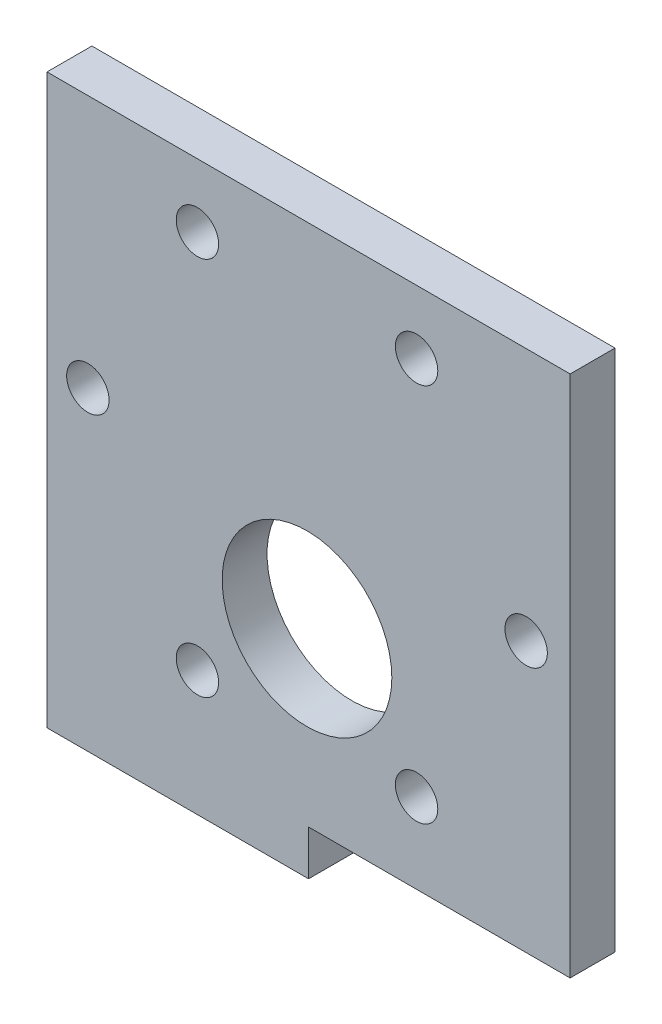
SolidWorks part; units mm, degrees
ref_plane "Front Plane" through (0, 0, 0) normal (0, 0, 1) x (1, 0, 0)
ref_plane "Top Plane" through (0, 0, 0) normal (0, 1, 0) x (1, 0, 0)
ref_plane "Right Plane" through (0, 0, 0) normal (1, 0, 0) x (0, 0, -1)
sketch "Sketch1" plane through (0, 0, 0) normal (0, 0, 1) x (1, 0, 0)
  line L0 (18.5, 0) -> (18.5, -3.175)
  line L1 (18.5, 0) -> (37, 0)
  line L2 (0, 0) -> (0, 37)
  line L3 (0, 37) -> (37, 37)
  line L4 (37, 0) -> (37, 37)
  line L5 (18.5, -3.175) -> (0, -3.175)
  line L6 (0, -3.175) -> (0, 0)
  line L7 (18.5, 0) -> (0, 0) construction
  line L8 (18.5, 0) -> (18.5, 11.35) construction
  line L10 (37, 0) -> (0, 37) construction
  circle A1 centre (18.3902, 12.0899) radius 6 construction
  circle A2 centre (18.3902, 12.0899) radius 6
  circle A3 centre (2.8902, 19.0899) radius 1.5 construction
  circle A4 centre (2.8902, 19.0899) radius 1.5
  circle A5 centre (10.6402, 5.6665) radius 1.5 construction
  circle A6 centre (10.6402, 5.6665) radius 1.5
  circle A7 centre (26.1402, 5.6665) radius 1.5 construction
  circle A8 centre (26.1402, 5.6665) radius 1.5
  circle A9 centre (33.8902, 19.0899) radius 1.5 construction
  circle A10 centre (33.8902, 19.0899) radius 1.5
  circle A11 centre (26.1402, 32.5133) radius 1.5 construction
  circle A12 centre (26.1402, 32.5133) radius 1.5
  circle A13 centre (10.6402, 32.5133) radius 1.5 construction
  circle A14 centre (10.6402, 32.5133) radius 1.5
  dimension "D1" = 37
  dimension "D2" = 37
  dimension "D3" = 3.175
extrude "Boss-Extrude1" add sketch "Sketch1" along normal blind 3.175
